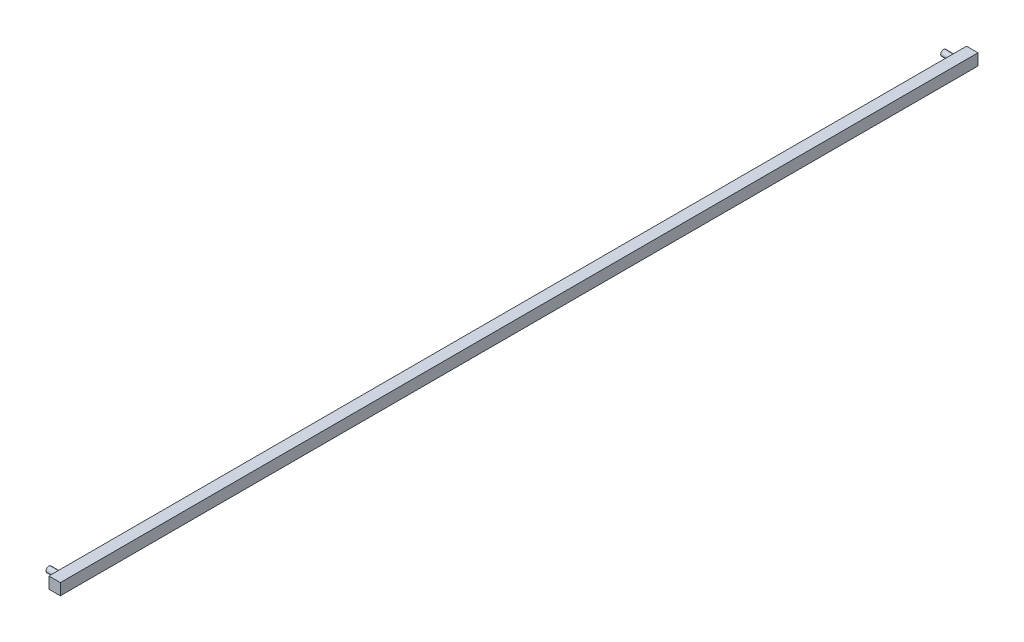
SolidWorks part; units mm, degrees
ref_plane "Front Plane" through (0, 0, 0) normal (0, 0, 1) x (1, 0, 0)
ref_plane "Top Plane" through (0, 0, 0) normal (0, 1, 0) x (1, 0, 0)
ref_plane "Right Plane" through (0, 0, 0) normal (1, 0, 0) x (0, 0, -1)
sketch "Sketch1" plane through (0, 0, 0) normal (0, 0, 1) x (1, 0, 0)
  line L1 (-5, -5) -> (5, -5)
  line L2 (-5, -5) -> (-5, 5)
  line L3 (-5, 5) -> (5, 5)
  line L4 (5, -5) -> (5, 5)
  line L5 (-5, -5) -> (5, 5) construction
  line L6 (-5, 5) -> (5, -5) construction
  point P0 (0, 0)
  dimension "D1" = 10
  dimension "D2" = 10
extrude "Boss-Extrude1" add sketch "Sketch1" along normal blind 800
sketch "Sketch4" plane through (-5, 0, 0) normal (-1, 0, 0) x (0, 0, 1)
  line L0 (0, 0) -> (10, 0)
  line L1 (800, 0) -> (790, 0)
  line L2 (800, 5) -> (800, -5) construction
  circle A0 centre (10, 0) radius 2.5
  circle A1 centre (790, 0) radius 2.5
  dimension "D2" = 5
  dimension "D4" = 5
  dimension "D1" = 10
  dimension "D3" = 10
extrude "Boss-Extrude3" add sketch "Sketch4" along normal blind 10
